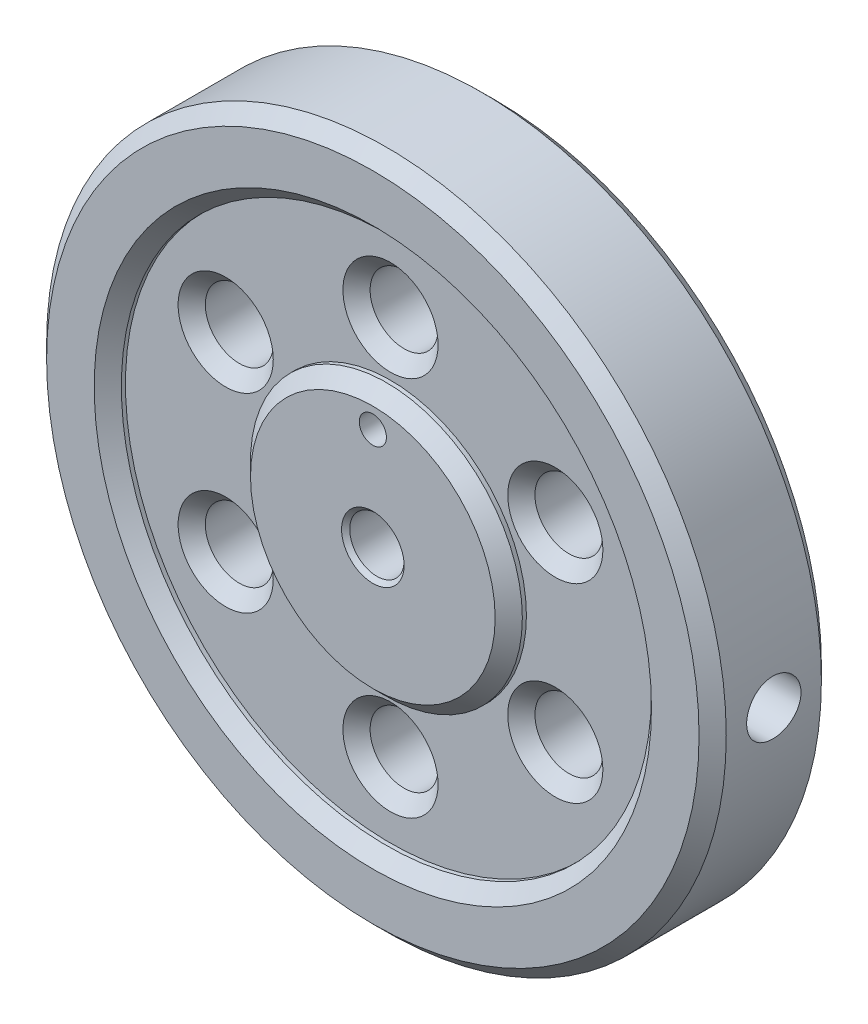
SolidWorks part; units mm, degrees
material "6061-T4 (SS)"
ref_plane "前视基准面" through (0, 0, 0) normal (0, 0, 1) x (1, 0, 0)
ref_plane "上视基准面" through (0, 0, 0) normal (0, 1, 0) x (1, 0, 0)
ref_plane "右视基准面" through (0, 0, 0) normal (1, 0, 0) x (0, 0, -1)
sketch "草图1" plane through (0, 0, 0) normal (0, 0, 1) x (1, 0, 0)
  circle A0 centre (0, 0) radius 25
  dimension "D1" = 50
extrude "凸台-拉伸1" add sketch "草图1" along normal mid plane 9
sketch "草图2" plane through (0, 0, 4.5) normal (0, 0, 1) x (1, 0, 0)
  circle A0 centre (0, 0) radius 2
  dimension "D1" = 4
extrude "切除-拉伸1" cut sketch "草图2" against normal through all
chamfer "倒角1" distance 1 angle 45 2 edges at (25, 0, -4.5) (25, 0, 4.5)
sketch "草图3" plane through (0, 0, 4.5) normal (0, 0, 1) x (1, 0, 0)
  circle A0 centre (0, 0) radius 10
  circle A1 centre (0, 0) radius 19.5
  dimension "D1" = 20
  dimension "D2" = 39
extrude "切除-拉伸2" cut sketch "草图3" against normal blind 1.3
chamfer "倒角2" distance 1 angle 45 1 edges at (19.5, 0, 4.5)
chamfer "倒角3" distance 1 angle 45 1 edges at (10, 0, 4.5)
sketch "草图4" plane through (0, 0, 4.5) normal (0, 0, 1) x (1, 0, 0)
  circle A0 centre (0, 7.5) radius 1
  dimension "D1" = 2
  dimension "D2" = 7.5
extrude "切除-拉伸3" cut sketch "草图4" against normal blind 2
chamfer "倒角4" distance 0.3 angle 45 2 edges at (2, 0, 4.5) (2, 0, -4.5)
mirror "镜向3" about plane through (0, 0, 0) normal (0, 0, 1) of "切除-拉伸2"
chamfer "倒角5" distance 1 angle 45 2 edges at (10, 0, -4.5) (19.5, 0, -4.5)
sketch "草图5" plane through (0, 0, -4.5) normal (0, 0, -1) x (-1, 0, 0)
  circle A0 centre (0, 0) radius 3.5
  circle A1 centre (0, 0) radius 8
  dimension "D1" = 16
  dimension "D2" = 7
extrude "切除-拉伸4" cut sketch "草图5" against normal blind 0.3
sketch "草图6" plane through (0, 0, 3.2) normal (0, 0, 1) x (1, 0, 0)
  circle A0 centre (0, 0) radius 14 construction
  circle A1 centre (0, 14) radius 2.5
  circle A2 centre (12.1244, 7) radius 2.5
  circle A3 centre (12.1244, -7) radius 2.5
  circle A4 centre (0, -14) radius 2.5
  circle A5 centre (-12.1244, -7) radius 2.5
  circle A6 centre (-12.1244, 7) radius 2.5
  point P17 (0, 0)
  dimension "D1" = 5
  dimension "D3" = 28
  dimension "D2" = 6
extrude "切除-拉伸5" cut sketch "草图6" against normal through all
chamfer "倒角6" distance 1 angle 45 12 edges at (14.6244, 7, 3.2) (9.6244, 7, -3.2) (14.6244, -7, 3.2) (9.6244, -7, -3.2) (2.5, -14, 3.2) (-2.5, -14, -3.2) (-9.6244, -7, 3.2) (-14.6244, -7, -3.2) (-9.6244, 7, 3.2) (-14.6244, 7, -3.2) (2.5, 14, 3.2) (-2.5, 14, -3.2)
sketch "草图7" plane through (0, 0, 0) normal (1, 0, 0) x (0, 0, -1)
  circle A0 centre (0, 0) radius 2
  dimension "D1" = 4
extrude "切除-拉伸6" cut sketch "草图7" along normal blind 20 from offset 10
sketch "草图8" plane through (10, 0, 0) normal (1, 0, 0) x (0, 0, -1)
  circle A0 centre (0, 0) radius 1.5
  dimension "D1" = 3
extrude "切除-拉伸7" cut sketch "草图8" against normal up to next
